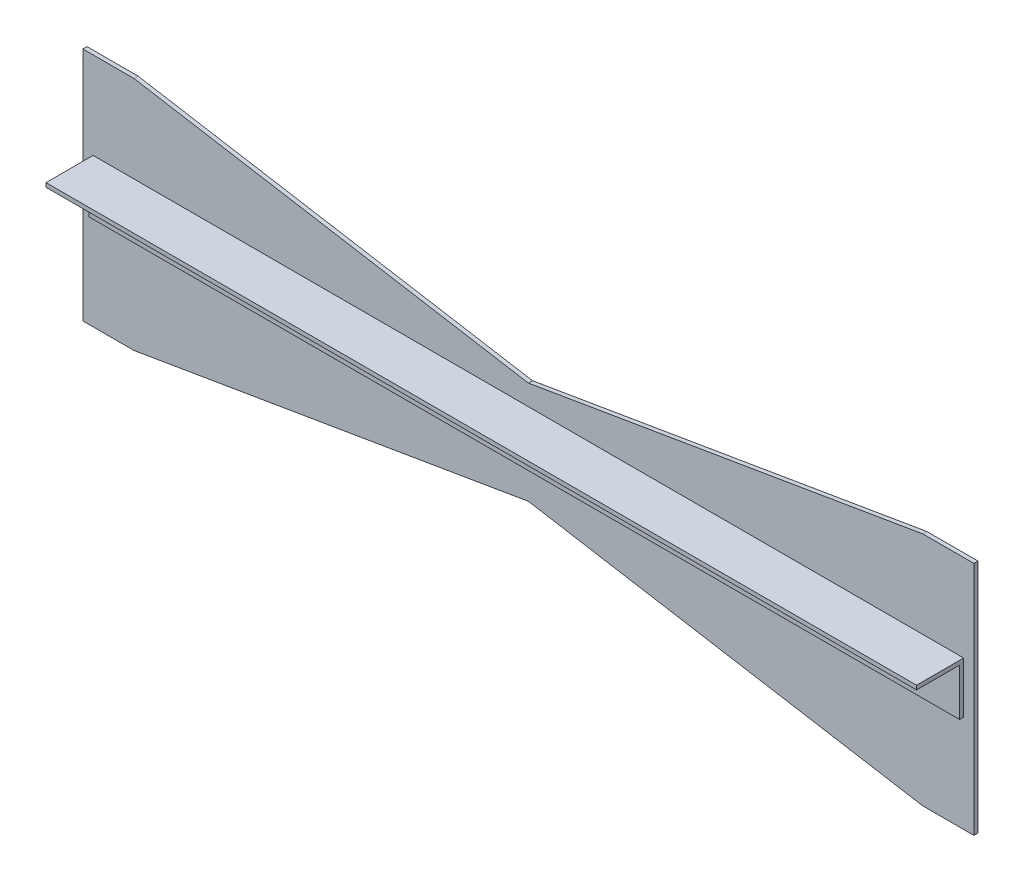
SolidWorks part; units mm, degrees
ref_plane "前视基准面" through (0, 0, 0) normal (0, 0, 1) x (1, 0, 0)
ref_plane "上视基准面" through (0, 0, 0) normal (0, 1, 0) x (1, 0, 0)
ref_plane "右视基准面" through (0, 0, 0) normal (1, 0, 0) x (0, 0, -1)
sketch "草图1" plane through (0, 0, 0) normal (0, 0, 1) x (1, 0, 0)
  line L0 (-1000, 0) -> (49000, 0) construction
  line L1 (0, -1000) -> (0, 49000) construction
  line L2 (-870, 0) -> (-870, 230)
  line L3 (-870, 230) -> (-770, 230)
  line L4 (-1729.4208, 100) -> (48270.5792, 100) construction
  line L5 (-770, 230) -> (0, 100)
  line L6 (0, 100) -> (0, 0)
  line L7 (0, 0) -> (-870, 0)
  line L8 (-850, -820.3235) -> (-850, 49179.6765) construction
  line L9 (-800, -817.1359) -> (-800, 49182.8641) construction
  line L10 (-1850, 60) -> (48150, 60) construction
  line L11 (-1694.3572, -40) -> (48305.6428, -40) construction
  line L12 (-2105.5569, 52) -> (47894.4431, 52) construction
  line L13 (-640, -833.9651) -> (-640, 49166.0349) construction
  line L14 (-640, 0) -> (-870, 230) construction
  point P9 (0, 100)
  point P22 (-800, 0)
  point P25 (-640, 0)
  point P28 (-770.8855, 130.8855)
  point P29 (-827.454, 187.454)
  dimension "D1" = 230
  dimension "D2" = 870
  dimension "D3" = 100
  dimension "D4" = 100
  dimension "D5" = 20
  dimension "D6" = 50
  dimension "D7" = 60
  dimension "D8" = 40
  dimension "D9" = 8
  dimension "D10" = 160
  dimension "D11" = 185.1
  dimension "D12" = 80
extrude "凸台-拉伸2" add sketch "草图1" along normal blind 8
mirror "镜向2" about plane through (0, 0, 0) normal (0, 1, 0) of "凸台-拉伸2"
sketch "草图5" plane through (0, 0, 8) normal (0, 0, 1) x (1, 0, 0)
  line L0 (-1000, 0) -> (49000, 0) construction
  line L1 (-1669.8613, 60) -> (48330.1387, 60) construction
  line L2 (-1615.3919, 52) -> (48384.6081, 52) construction
  line L3 (-1765.1827, -40) -> (48234.8173, -40) construction
  line L4 (-850, -975.26) -> (-850, 49024.74) construction
  line L5 (-870, 230) -> (-870, -230) construction
  line L6 (-800, -901.9358) -> (-800, 49098.0642) construction
  line L7 (-850, -40) -> (0, -40)
  line L8 (0, -40) -> (0, 60)
  line L9 (0, -100) -> (0, 100) construction
  line L10 (0, 60) -> (-850, 60)
  line L11 (-850, 60) -> (-850, -40)
  dimension "D1" = 60
  dimension "D2" = 8
  dimension "D3" = 40
  dimension "D4" = 20
  dimension "D5" = 50
extrude "凸台-拉伸3" add sketch "草图5" along normal blind 8
sketch "草图6" plane through (0, 0, 16) normal (0, 0, 1) x (1, 0, 0)
  line L0 (-850, 52) -> (0, 52) construction
  line L1 (-850, 60) -> (-850, -40) construction
  line L2 (0, 60) -> (-850, 60) construction
  line L3 (-850, 60) -> (-850, 52)
  line L4 (-850, 52) -> (0, 52)
  line L5 (0, 52) -> (0, 60)
  line L6 (0, 60) -> (-850, 60)
  dimension "D1" = 8
extrude "凸台-拉伸4" add sketch "草图6" along normal blind 84
mirror "镜向7" about plane through (0, 0, 0) normal (1, 0, 0) of "凸台-拉伸4", "凸台-拉伸3", "镜向2", "凸台-拉伸2"
